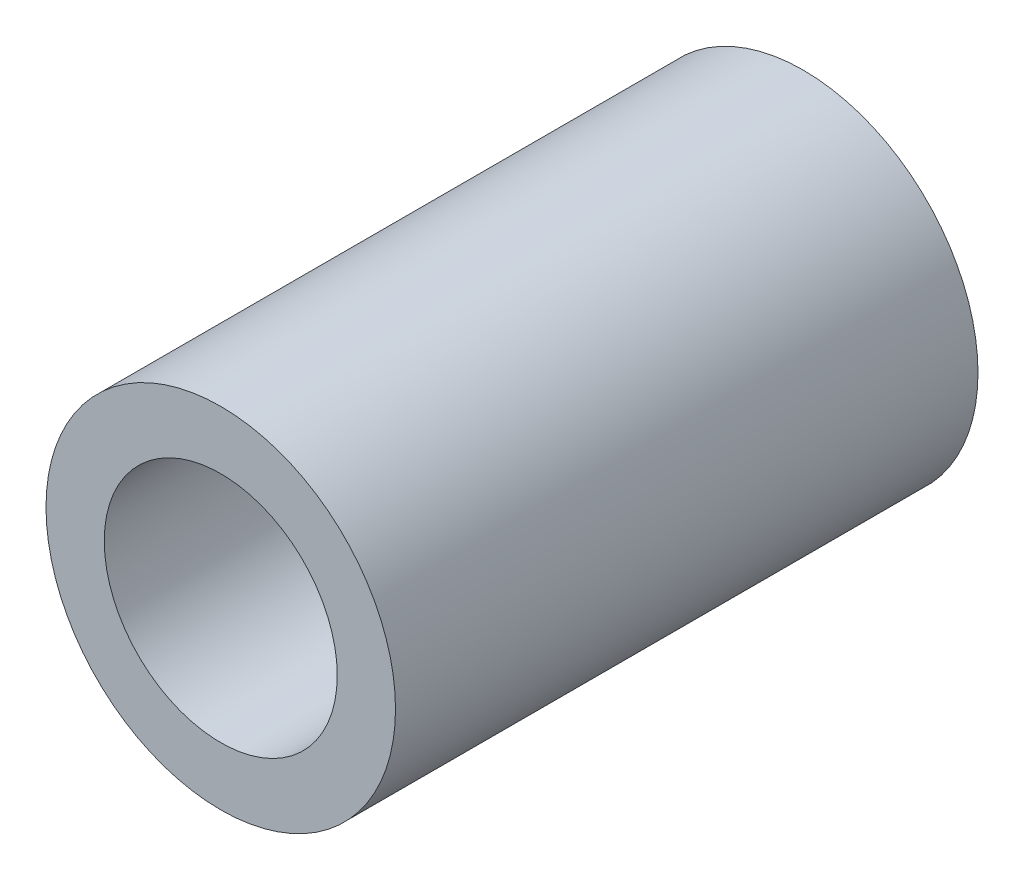
SolidWorks part; units mm, degrees
ref_plane "Plano frontal" through (0, 0, 0) normal (0, 0, 1) x (1, 0, 0)
ref_plane "Plano superior" through (0, 0, 0) normal (0, 1, 0) x (1, 0, 0)
ref_plane "Plano direito" through (0, 0, 0) normal (1, 0, 0) x (0, 0, -1)
sketch "Esboço1" plane through (0, 0, 0) normal (0, 0, 1) x (1, 0, 0)
  circle A0 centre (0, 0) radius 4.5
extrude "Ressalto-extrusão1" add sketch "Esboço1" along normal blind 15
sketch "Esboço2" plane through (0, 0, 15) normal (0, 0, 1) x (1, 0, 0)
  circle A0 centre (0, 0) radius 3
extrude "Corte-extrusão1" cut sketch "Esboço2" against normal blind 5
sketch "Esboço3" plane through (0, 0, 0) normal (0, 0, -1) x (-1, 0, 0)
  circle A0 centre (0, 0) radius 2
extrude "Corte-extrusão2" cut sketch "Esboço3" against normal blind 5
